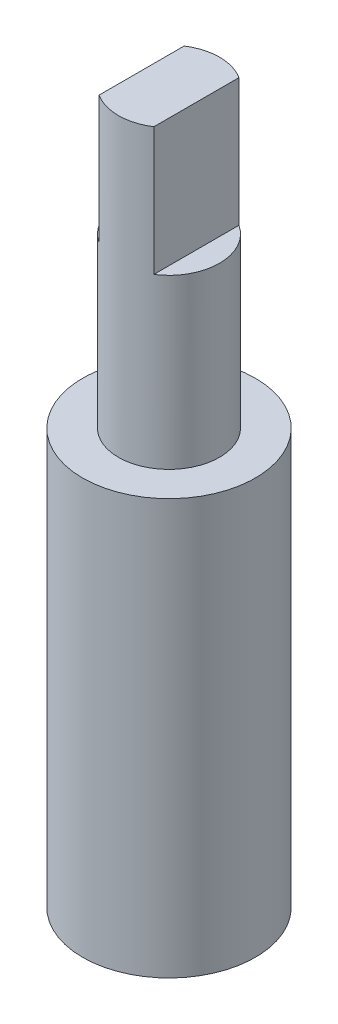
SolidWorks part; units mm, degrees
ref_plane "Front Plane" through (0, 0, 0) normal (0, 0, 1) x (1, 0, 0)
ref_plane "Top Plane" through (0, 0, 0) normal (0, 1, 0) x (1, 0, 0)
ref_plane "Right Plane" through (0, 0, 0) normal (1, 0, 0) x (0, 0, -1)
sketch "Sketch1" plane through (0, 0, 0) normal (0, 1, 0) x (1, 0, 0)
  circle A0 centre (0, 0) radius 3.075
  dimension "D1" = 6.15
extrude "Boss-Extrude1" add sketch "Sketch1" along normal blind 14.77
sketch "Sketch2" plane through (0, 14.77, 0) normal (0, 1, 0) x (1, 0, 0)
  circle A0 centre (0, 0) radius 1.8
  dimension "D1" = 3.6
extrude "Boss-Extrude2" add sketch "Sketch2" along normal blind 5.98
sketch "Sketch3" plane through (0, 20.75, 0) normal (0, 1, 0) x (1, 0, 0)
  line L0 (-0.975, 1.5131) -> (-0.975, -1.5131)
  line L1 (0.975, 1.5131) -> (0.975, -1.5131)
  circle A0 centre (0, 0) radius 1.8 construction
  circle A1 centre (0, 0) radius 1.8 construction
  arc A2 (-0.975, -1.5131) -> (0.975, -1.5131) centre (0, 0) ccw
  arc A3 (0.975, 1.5131) -> (-0.975, 1.5131) centre (0, 0) ccw
  point P4 (-1.8, 0)
  point P5 (1.8, 0)
  dimension "D1" = 1.95
  dimension "D2" = 0.975
extrude "Boss-Extrude3" add sketch "Sketch3" along normal blind 4.55
sketch "Sketch4" plane through (0, 0, 0) normal (0, -1, 0) x (1, 0, 0)
  circle A0 centre (0, 0) radius 2.15
  dimension "D1" = 4.3
extrude "Cut-Extrude1" cut sketch "Sketch4" against normal blind 1.95
